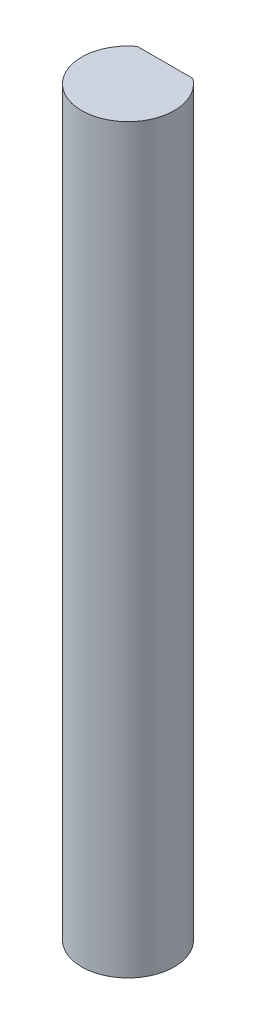
SolidWorks part; units mm, degrees
ref_plane "Front Plane" through (0, 0, 0) normal (0, 0, 1) x (1, 0, 0)
ref_plane "Top Plane" through (0, 0, 0) normal (0, 1, 0) x (1, 0, 0)
ref_plane "Right Plane" through (0, 0, 0) normal (1, 0, 0) x (0, 0, -1)
sketch "Sketch1" plane through (0, 0, 0) normal (0, 1, 0) x (1, 0, 0)
  circle A0 centre (0, 0) radius 3.175
  dimension "D1" = 6.35
extrude "Boss-Extrude1" add sketch "Sketch1" along normal blind 50.8
sketch "Sketch2" plane through (0, 0, 0) normal (0, -1, 0) x (1, 0, 0)
  line L0 (1.905, -2.54) -> (-1.905, -2.54)
  line L1 (0, 0) -> (0, -2.54) construction
  circle A0 centre (0, 0) radius 3.175 construction
  arc A1 (-1.905, -2.54) -> (1.905, -2.54) centre (0, 0) ccw
  dimension "D1" = 5.715
extrude "Cut-Extrude1" cut sketch "Sketch2" against normal through all
